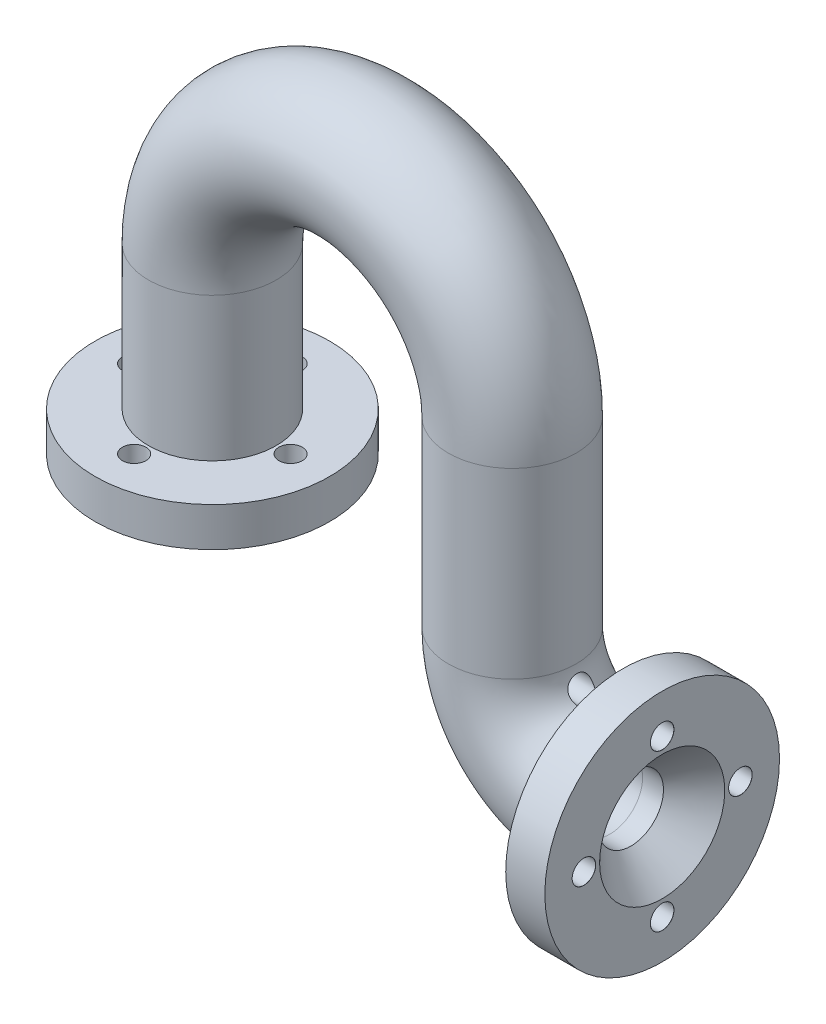
SolidWorks part; units mm, degrees
ref_plane "Front Plane" through (0, 0, 0) normal (0, 0, 1) x (1, 0, 0)
ref_plane "Top Plane" through (0, 0, 0) normal (0, 1, 0) x (1, 0, 0)
ref_plane "Right Plane" through (0, 0, 0) normal (1, 0, 0) x (0, 0, -1)
sketch "Sketch1" plane through (0, 0, 0) normal (0, 0, 1) x (1, 0, 0)
  line L0 (0, 0) -> (0, 70)
  line L1 (115, 70) -> (115, 0)
  line L2 (152.5, -37.5) -> (157.5, -37.5)
  arc A0 (0, 70) -> (115, 70) centre (57.5, 70) cw
  arc A1 (115, 0) -> (152.5, -37.5) centre (152.5, 0) ccw
  dimension "D2" = 57.5
  dimension "D4" = 37.5
  dimension "D1" = 70
  dimension "D3" = 42.5
sketch "Sketch2" plane through (0, 0, 0) normal (0, 1, 0) x (1, 0, 0)
  circle A0 centre (0, 0) radius 24.5
  circle A1 centre (0, 0) radius 12.5
  dimension "D1" = 49
  dimension "D2" = 25
sweep "Sweep1" add profiles "Sketch2" path "Sketch1"
sketch "Sketch3" plane through (157.5, 0, 0) normal (1, 0, 0) x (0, 0, -1)
  circle A0 centre (0, -37.5) radius 12.5 construction
  circle A1 centre (0, -37.5) radius 12.5
  circle A2 centre (0, -37.5) radius 45
  dimension "D1" = 90
extrude "Boss-Extrude1" add sketch "Sketch3" along normal blind 15
sketch "Sketch4" plane through (0, 0, 0) normal (0, -1, 0) x (-1, 0, 0)
  circle A0 centre (0, 0) radius 45
  circle A1 centre (0, 0) radius 12.5 construction
  circle A2 centre (0, 0) radius 12.5
  dimension "D1" = 90
extrude "Boss-Extrude2" add sketch "Sketch4" against normal blind 15
hole_wizard "Tap Drill for M10x1.0 Tap1" positions "Sketch9" profile "Sketch10" hole size "M10x1.0" standard "ISO"
sketch "Sketch9" plane through (0, 0, 0) normal (0, -1, 0) x (-1, 0, 0)
  point P0 (30, 0)
  point P4 (0, 0)
  dimension "D1" = 30
sketch "Sketch10" plane through (-30, 0, 0) normal (1, 0, 0) x (0, 0, -1)
  line L0 (0, 0) -> (0, 72.7039)
  line L1 (0, 72.7039) -> (4.5, 70)
  line L2 (4.5, 70) -> (4.5, 0.025)
  line L3 (4.5, 0.025) -> (4.525, 0)
  line L5 (4.525, 0) -> (0, 0)
  line L6 (-4.5, 0.025) -> (-4.525, 0) construction
  line L10 (0, 72.7039) -> (-4.5, 70) construction
  line L11 (0, -6.35) -> (0, 107.95) construction
  dimension "Hole Dia." = 9
  dimension "Hole Depth" = 70
  dimension "Near C'Sink Dia." = 9.05
  dimension "Near C'Sink Angle" = 90
  dimension "Drill Angle" = 118
pattern_circular "CirPattern1" count 4 over 360 about axis through (0, 0, 0) along (0, 1, 0) of "Tap Drill for M10x1.0 Tap1"
hole_wizard "Tap Drill for M10x1.0 Tap2" positions "Sketch11" profile "Sketch12" hole size "M10x1.0" standard "ISO"
sketch "Sketch11" plane through (172.5, 0, 0) normal (1, 0, 0) x (0, 0, -1)
  line L0 (0, -37.5) -> (30, -37.5) construction
  point P0 (30, -37.5)
  dimension "D1" = 30
sketch "Sketch12" plane through (172.5, -37.5, -30) normal (0, 1, 0) x (0, 0, -1)
  line L0 (0, 0) -> (0, 72.7039)
  line L1 (0, 72.7039) -> (4.5, 70)
  line L2 (4.5, 70) -> (4.5, 0.025)
  line L3 (4.5, 0.025) -> (4.525, 0)
  line L5 (4.525, 0) -> (0, 0)
  line L6 (-4.5, 0.025) -> (-4.525, 0) construction
  line L10 (0, 72.7039) -> (-4.5, 70) construction
  line L11 (0, -6.35) -> (0, 107.95) construction
  dimension "Hole Dia." = 9
  dimension "Hole Depth" = 70
  dimension "Near C'Sink Dia." = 9.05
  dimension "Near C'Sink Angle" = 90
  dimension "Drill Angle" = 118
pattern_circular "CirPattern2" count 4 over 360 about axis through (0, -37.5, 0) along (1, 0, 0) of "Tap Drill for M10x1.0 Tap2"
sketch "Sketch15" plane through (0, 0, 0) normal (0, 0, 1) x (1, 0, 0)
  line L0 (157.5, -37.5) -> (184.0167, -37.5) construction
  line L1 (157.5, 7.5) -> (157.5, -82.5) construction
  line L2 (160.5, -37.5) -> (160.5, -25)
  line L3 (160.5, -25) -> (172.5, -13.5)
  line L4 (172.5, -82.5) -> (172.5, 7.5) construction
  line L5 (172.5, -13.5) -> (172.5, -37.5)
  line L6 (172.5, -37.5) -> (160.5, -37.5)
  dimension "D1" = 24
  dimension "D2" = 12
  dimension "D3" = 12.5
revolve "Cut-Revolve1" cut sketch "Sketch15" angle 360 about L0
sketch "Sketch16" plane through (0, 0, 0) normal (1, 0, 0) x (0, 0, -1)
  line L0 (0, 0) -> (0, 12)
  line L1 (0, 12) -> (-12.5, 12)
  line L2 (-12.5, 12) -> (-24, 0)
  line L3 (-45, 0) -> (45, 0) construction
  line L4 (-24, 0) -> (0, 0)
  line L5 (0, 0) -> (0, 51.0213) construction
  dimension "D1" = 24
  dimension "D2" = 12
  dimension "D3" = 12.5
revolve "Cut-Revolve2" cut sketch "Sketch16" angle 360 about L5
